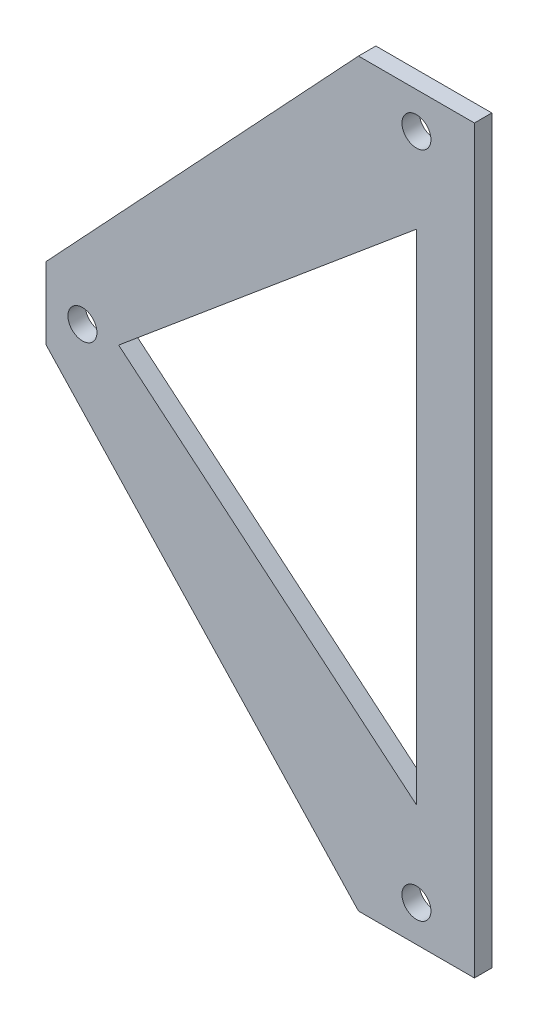
SolidWorks part; units mm, degrees
ref_plane "Front Plane" through (0, 0, 0) normal (0, 0, 1) x (1, 0, 0)
ref_plane "Top Plane" through (0, 0, 0) normal (0, 1, 0) x (1, 0, 0)
ref_plane "Right Plane" through (0, 0, 0) normal (1, 0, 0) x (0, 0, -1)
sketch "Sketch1" plane through (0, 0, 0) normal (0, 0, 1) x (1, 0, 0)
  line L4 (31.7324, 76.6602) -> (39.7324, 76.6602)
  line L5 (39.7324, 76.6602) -> (39.7324, 81.6602)
  line L6 (39.7324, 81.6602) -> (31.7324, 81.6602)
  line L7 (31.7324, 81.6602) -> (31.7324, 76.6602)
  line L8 (31.7324, 76.6602) -> (39.7324, 76.6602)
  line L9 (39.7324, 76.6602) -> (39.7324, 81.6602)
  line L10 (39.7324, 81.6602) -> (31.7324, 81.6602)
  line L11 (31.7324, 81.6602) -> (31.7324, 76.6602)
  line L12 (15.1824, 104.7102) -> (10.1824, 104.7102)
  line L13 (10.1824, 104.7102) -> (10.1824, 99.7102)
  line L14 (10.1824, 99.7102) -> (15.1824, 99.7102)
  line L15 (15.1824, 99.7102) -> (15.1824, 104.7102)
  line L16 (15.1824, 104.7102) -> (10.1824, 104.7102)
  line L17 (10.1824, 104.7102) -> (10.1824, 99.7102)
  line L18 (10.1824, 99.7102) -> (15.1824, 99.7102)
  line L19 (15.1824, 99.7102) -> (15.1824, 104.7102)
  line L20 (31.7324, 122.7602) -> (39.7324, 122.7602)
  line L21 (39.7324, 122.7602) -> (39.7324, 127.7602)
  line L22 (39.7324, 127.7602) -> (31.7324, 127.7602)
  line L23 (31.7324, 127.7602) -> (31.7324, 122.7602)
  line L24 (31.7324, 122.7602) -> (39.7324, 122.7602)
  line L25 (39.7324, 122.7602) -> (39.7324, 127.7602)
  line L26 (39.7324, 127.7602) -> (31.7324, 127.7602)
  line L27 (31.7324, 127.7602) -> (31.7324, 122.7602)
  circle A0 centre (35.7324, 79.1602) radius 1 construction
  circle A1 centre (35.7324, 79.1602) radius 1
  circle A2 centre (12.6824, 102.2102) radius 1 construction
  circle A3 centre (12.6824, 102.2102) radius 1
  circle A4 centre (35.7324, 125.2602) radius 1 construction
  circle A5 centre (35.7324, 125.2602) radius 1
  dimension "D1" = 0
  dimension "D2" = 0
  dimension "D3" = 0
extrude "Boss-Extrude1" add sketch "Sketch1" along normal blind 1.2
sketch "Sketch2" plane through (0, 0, 1.2) normal (0, 0, 1) x (1, 0, 0)
  line L0 (10.1824, 99.7102) -> (31.7324, 76.6602)
  line L1 (15.1824, 102.2102) -> (39.7324, 81.6602)
  line L2 (15.1824, 99.7102) -> (15.1824, 104.7102) construction
  line L3 (15.1824, 102.2102) -> (39.7324, 122.7602)
  line L4 (10.1824, 104.7102) -> (31.7324, 127.7602)
  line L5 (39.7324, 122.7602) -> (39.7324, 81.6602)
  line L6 (35.7324, 122.7602) -> (35.7324, 81.6602)
  line L7 (31.7324, 122.7602) -> (39.7324, 122.7602) construction
  line L8 (39.7324, 81.6602) -> (31.7324, 81.6602) construction
  line L9 (31.7324, 81.6602) -> (31.7324, 76.6602) construction
  line L10 (31.7324, 81.6602) -> (31.7324, 76.6602)
  line L11 (39.7324, 81.6602) -> (31.7324, 81.6602)
  line L12 (10.1824, 99.7102) -> (15.1824, 99.7102) construction
  line L13 (10.1824, 99.7102) -> (15.1824, 99.7102)
  line L14 (31.7324, 127.7602) -> (31.7324, 122.7602) construction
  line L15 (15.1824, 104.7102) -> (10.1824, 104.7102) construction
  line L16 (31.7324, 122.7602) -> (39.7324, 122.7602)
  line L17 (31.7324, 127.7602) -> (31.7324, 122.7602)
  line L18 (15.1824, 99.7102) -> (15.1824, 104.7102)
  line L19 (15.1824, 104.7102) -> (10.1824, 104.7102)
  line L20 (10.1824, 104.7102) -> (10.1824, 99.7102) construction
  line L21 (10.1824, 104.7102) -> (10.1824, 99.7102)
  circle A0 centre (12.6824, 102.2102) radius 1 construction
  circle A1 centre (12.6824, 102.2102) radius 1
  line M1 (31.7324, 81.6602) -> (31.7324, 76.6602)
  line M4 (39.7324, 81.6602) -> (31.7324, 81.6602)
extrude "Boss-Extrude4" add sketch "Sketch2" against normal up to surface (1.2 mm away) contours L18 L13 L0 L6 L1 M1 M4 | L19 L18 L3 L6 L16 L17 L4 | L19 L21 L13 L18 A1 | L3 L6 L1 L5 | L16 L6 L3 | L1 L6 M4 up to face at (35.7324, 125.2602, 0)
